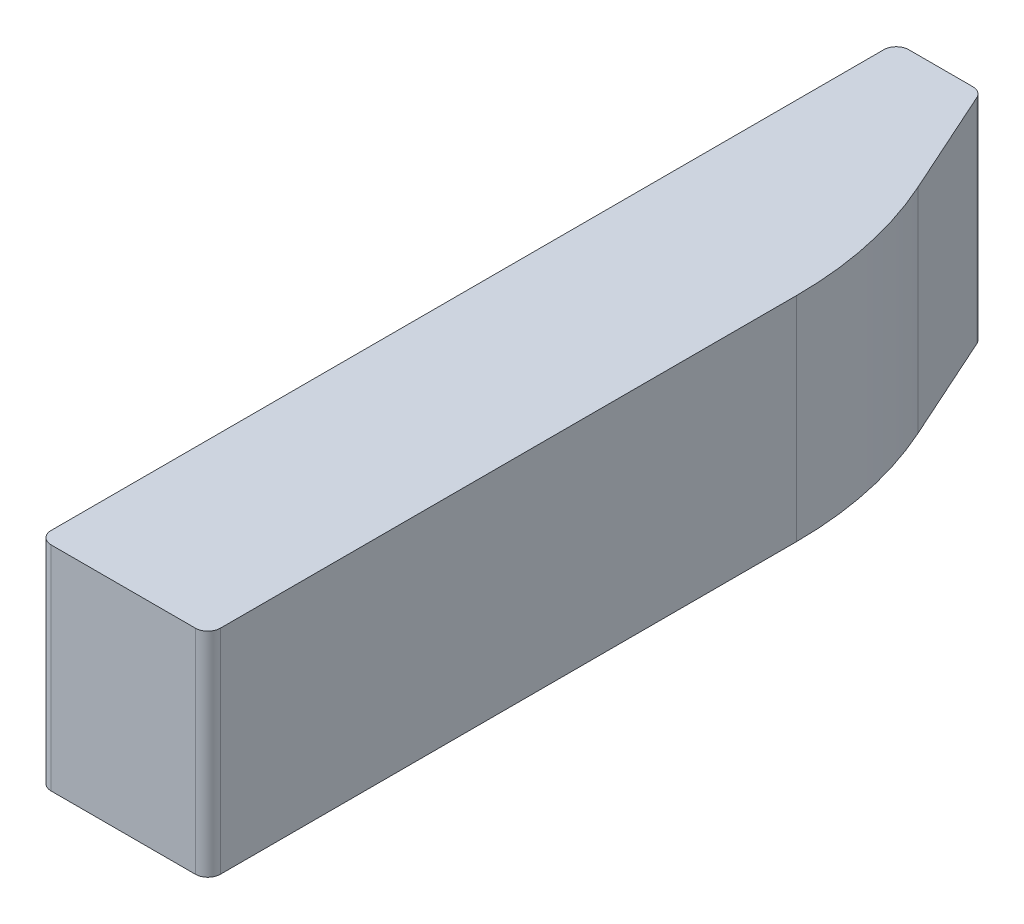
SolidWorks part; units mm, degrees
material "3DP"
ref_plane "正面" through (0, 0, 0) normal (0, 0, 1) x (1, 0, 0)
ref_plane "平面" through (0, 0, 0) normal (0, 1, 0) x (1, 0, 0)
ref_plane "右側面" through (0, 0, 0) normal (1, 0, 0) x (0, 0, -1)
sketch "ｽｹｯﾁ1" plane through (0, 0, 0) normal (0, 1, 0) x (1, 0, 0)
  line L1 (0, 0) -> (13.5, 0)
  line L2 (0, 0) -> (0, 68.4)
  line L3 (0, 68.4) -> (13.5, 68.4)
  line L4 (13.5, 0) -> (13.5, 68.4)
  dimension "D1" = 13.5
  dimension "D2" = 68.4
extrude "ﾎﾞｽ - 押し出し1" add sketch "ｽｹｯﾁ1" along normal blind 17
sketch "ｽｹｯﾁ2" plane through (0, 0, 0) normal (0, -1, 0) x (1, 0, 0)
  line L0 (8.5, 0) -> (8.5, -68.4) construction
  line L1 (0, 0) -> (13.5, 0) construction
  line L3 (13.5, -34.2) -> (0, -34.2) construction
  line L4 (13.5, 0) -> (13.5, -68.4) construction
  line L5 (0, -68.4) -> (0, 0) construction
  circle A0 centre (8.5, -47.4) radius 2.75
  circle A1 centre (8.5, -11) radius 2.75
  dimension "D1" = 5.5
  dimension "D2" = 36.4
  dimension "D3" = 11
  dimension "D4" = 5
extrude "ｶｯﾄ - 押し出し1" cut sketch "ｽｹｯﾁ2" against normal blind 5
sketch "ｽｹｯﾁ3" plane through (0, 17, 0) normal (0, 1, 0) x (1, 0, 0)
  line L0 (6.75, 68.4) -> (0, 68.4)
  line L1 (13.5, 68.4) -> (0, 68.4) construction
  line L2 (0, 68.4) -> (0, 53.4)
  line L3 (0, 68.4) -> (0, 0) construction
  line L4 (0, 53.4) -> (6.75, 68.4)
  dimension "D1" = 15
extrude "ｶｯﾄ - 押し出し2" cut sketch "ｽｹｯﾁ3" against normal up to surface (17 mm away) up to face at (8.5, 0, -50.15)
sketch "ｽｹｯﾁ4" plane through (0, 0, 0) normal (0, -1, 0) x (1, 0, 0)
  line L0 (0, -47) -> (-4, -37)
  line L1 (0, -53.4) -> (0, 0) construction
  line L2 (-4, -37) -> (-4, -27)
  line L3 (-4, -27) -> (0, -27)
  line L4 (0, -27) -> (0, -47)
  line L5 (0, 0) -> (13.5, 0) construction
  dimension "D1" = 4
  dimension "D2" = 20
  dimension "D3" = 10
  dimension "D4" = 27
extrude "ﾎﾞｽ - 押し出し2" add sketch "ｽｹｯﾁ4" against normal blind 5.5
sketch "ｽｹｯﾁ11" plane through (0, 17, 0) normal (0, 1, 0) x (1, 0, 0)
  line L0 (0, 53.4) -> (0, 0) construction
  line L1 (-4, 27) -> (0, 27)
  line L2 (-4, 27) -> (-4, 47)
  line L3 (-4, 47) -> (0, 47)
  line L4 (0, 27) -> (0, 47)
  point P4 (0, 0)
  point P6 (0, 30.4157)
  point P10 (0, 0)
  point P11 (-3.1587, 27)
extrude "ｶｯﾄ - 押し出し7" cut sketch "ｽｹｯﾁ11" against normal up to surface (17 mm away) up to face at (2.8611, 0, -36.4667)
fillet "ﾌｨﾚｯﾄ1" radius 30 1 edges at (0, 8.5, -53.4)
fillet "ﾌｨﾚｯﾄ2" radius 1 4 edges at (0, 8.5, 0) (13.5, 8.5, 0) (13.5, 8.5, -68.4) (6.75, 8.5, -68.4)
ref_plane "平面1" through (-10, 0, 0) normal (-1, 0, 0) x (0, 0, 1)
mirror "ﾐﾗｰ1" about plane through (-10, 0, 0) normal (-1, 0, 0) of bodies 109 105
sketch "ｽｹｯﾁ7" plane through (0, 17, 0) normal (0, 1, 0) x (1, 0, 0)
  line L0 (1, 0) -> (12.5, 0) construction
  line L1 (-16.5, 69.0533) -> (13.5, 69.0533)
  line L2 (-16.5, 69.0533) -> (-16.5, 0)
  line L3 (-16.5, 0) -> (13.5, 0)
  line L4 (13.5, 69.0533) -> (13.5, 0)
  line L5 (13.5, 1) -> (13.5, 67.4) construction
  dimension "D1" = 30
  dimension "D2" = 69.0533
extrude "ｶｯﾄ - 押し出し4" cut sketch "ｽｹｯﾁ7" against normal up to surface (17 mm away) contours L2 L1 L4 L3 up to face at (6.8991, 0, -38.0311)
